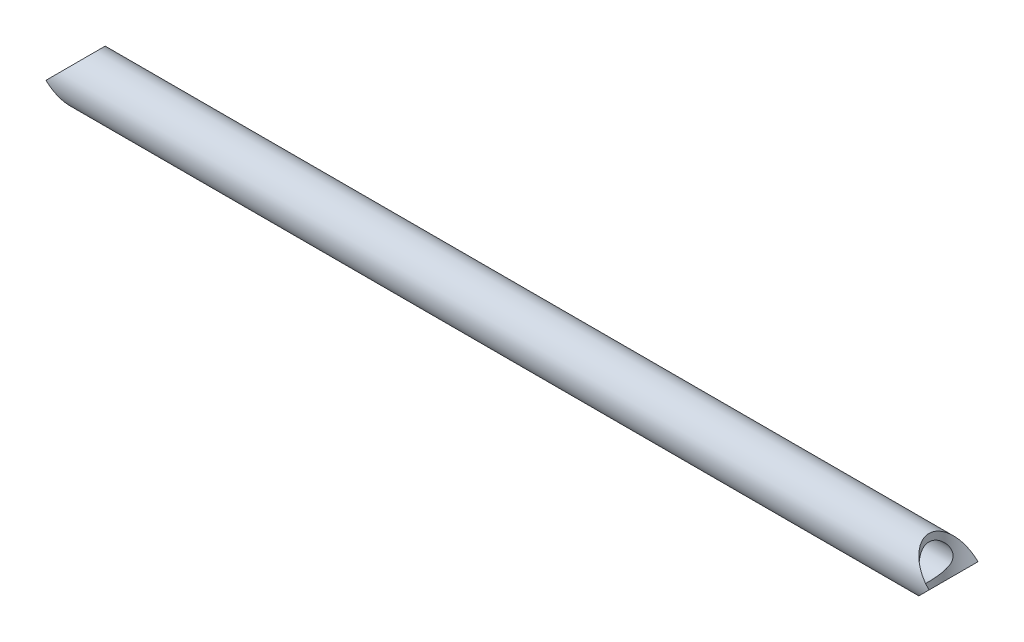
SolidWorks part; units mm, degrees
ref_plane "Front Plane" through (0, 0, 0) normal (0, 0, 1) x (1, 0, 0)
ref_plane "Top Plane" through (0, 0, 0) normal (0, 1, 0) x (1, 0, 0)
ref_plane "Right Plane" through (0, 0, 0) normal (1, 0, 0) x (0, 0, -1)
sketch "Sketch1" plane through (0, 0, 0) normal (0, 1, 0) x (1, 0, 0)
  line L0 (-900, 0) -> (900, 0)
  point P3 (0, 0)
  dimension "D1" = 1800
sketch "Sketch2" plane through (0, 0, 0) normal (1, 0, 0) x (0, 0, -1)
  circle A0 centre (0, 0) radius 50
  circle A1 centre (0, 0) radius 35
  dimension "D1" = 100
  dimension "D2" = 15
sweep "Sweep1" add profiles "Sketch2" path "Sketch1"
sketch "Sketch3" plane through (0, 0, 0) normal (0, 1, 0) x (1, 0, 0)
  line L0 (900, -50) -> (900, 50) construction
  line L1 (-900, 50) -> (-900, -50) construction
  circle A0 centre (900, 0) radius 50
  circle A1 centre (-900, 0) radius 50
  dimension "D1" = 100
  dimension "D2" = 100
extrude "Cut-Extrude1" cut sketch "Sketch3" against normal through all both and the other way through all
equation "\"hatchHoleDiameter\"= 600mm"
equation "\"hullThickness\"= 120mm"
equation "\"gasketHullInterconnectWidth\"= 100mm"
equation "\"collarThickness\"= 15"
equation "\"hatchTunnelLength\"=200"
equation "\"oRingDiameter\"=2"
equation "\"boltPatternRadiusInterconnect\"=500"
equation "\"interconnectBoltDiameter\"=30"
equation "\"hatchShaftDiameter\"=20"
equation "\"hatchMinima\"=50"
equation "\"hullDiameter\"=2000"
equation "\"hatchMaxima\"=180"
equation "\"bushingFlatHatch\"=15"
equation "\"hingePivotDiameter\"=20"
equation "\"handleWidth\"=250"
equation "\"handleHeight\"=160"
equation "\"handleThickness\"=25"
equation "\"FrameLength\"= 4300"
equation "\"FrameMidLength\"= 3000"
equation "\"TubeOD\"= 100"
equation "\"FrameBackFlat\"= 800"
equation "\"TubeWall\"=15"
equation "\"TopMemberAngle\"=120"
equation "\"FrameHight\"= 2500"
equation "\"D1@Sketch1\"=\"hullDiameter\" *.9"
equation "\"D1@Sketch2\"=\"TubeOD\""
equation "\"D2@Sketch2\"=\"TubeWall\""
equation "\"D1@Sketch3\"=\"TubeOD\""
equation "\"D2@Sketch3\"=\"TubeOD\""
